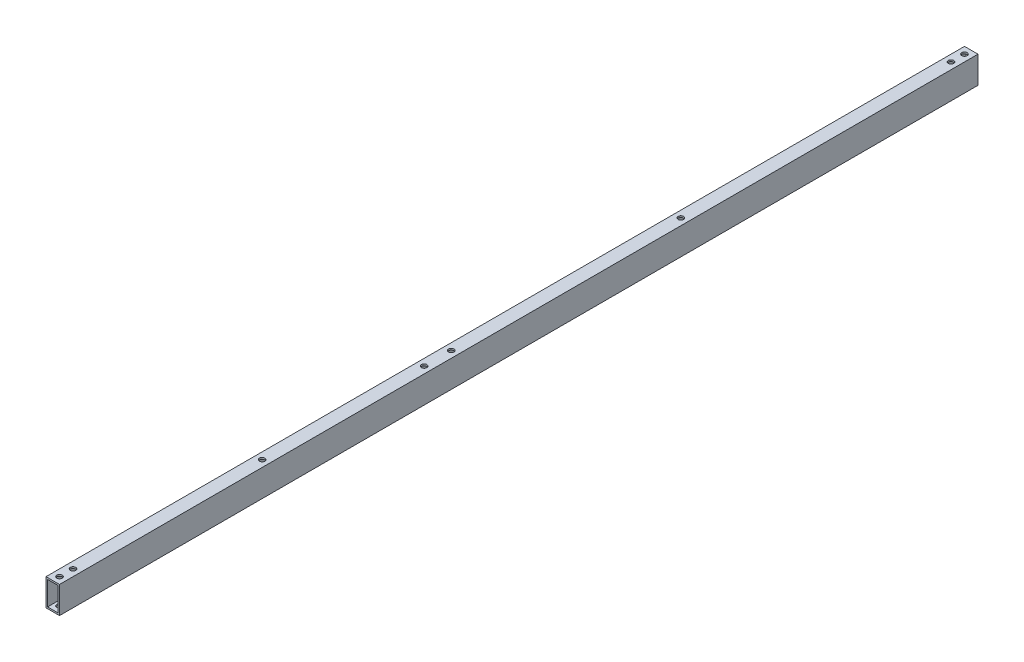
SolidWorks part; units mm, degrees
material "5052-H34"
ref_plane "正面" through (0, 0, 0) normal (0, 0, 1) x (1, 0, 0)
ref_plane "平面" through (0, 0, 0) normal (0, 1, 0) x (1, 0, 0)
ref_plane "右側面" through (0, 0, 0) normal (1, 0, 0) x (0, 0, -1)
sketch "ｽｹｯﾁ1" plane through (0, 0, 0) normal (0, 0, 1) x (1, 0, 0)
  line L1 (-5, 10) -> (5, 10)
  line L2 (-5, 10) -> (-5, -10)
  line L3 (-5, -10) -> (5, -10)
  line L4 (5, 10) -> (5, -10)
  line L5 (-5, 10) -> (5, -10) construction
  line L6 (-5, -10) -> (5, 10) construction
  point P0 (0, 0)
  dimension "D1" = 10
  dimension "D2" = 20
extrude "押し出し-薄板1" add sketch "ｽｹｯﾁ1" along normal blind 680 thin
sketch "ｽｹｯﾁ2" plane through (0, 10, 0) normal (0, 1, 0) x (1, 0, 0)
  line L0 (-5, -340) -> (5, -340) construction
  line L1 (-5, -680) -> (-5, 0) construction
  line L2 (5, -680) -> (5, 0) construction
  line L3 (0, -680) -> (0, -665) construction
  line L4 (5, -680) -> (-5, -680) construction
  line L5 (0, -525) -> (0, -665) construction
  line L6 (0, -525) -> (0, -405) construction
  line L7 (0, 0) -> (0, -215) construction
  circle A0 centre (0, -665) radius 2
  circle A1 centre (0, -675) radius 2
  circle A2 centre (0, -5) radius 2
  circle A3 centre (0, -15) radius 2
  circle A4 centre (0, -525) radius 2
  circle A5 centre (0, -405) radius 2
  circle A6 centre (0, -215) radius 2
  circle A7 centre (0, -385) radius 2
  point P28 (0, -392.2675)
  dimension "D1" = 4
  dimension "D5" = 4
  dimension "D9" = 4
  dimension "D10" = 4
  dimension "D2" = 5
  dimension "D3" = 10
  dimension "D4" = 155
  dimension "D7" = 120
  dimension "D8" = 215
  dimension "D11" = 20
  dimension "D6" = 2
extrude "ｶｯﾄ - 押し出し1" cut sketch "ｽｹｯﾁ2" against normal through all
